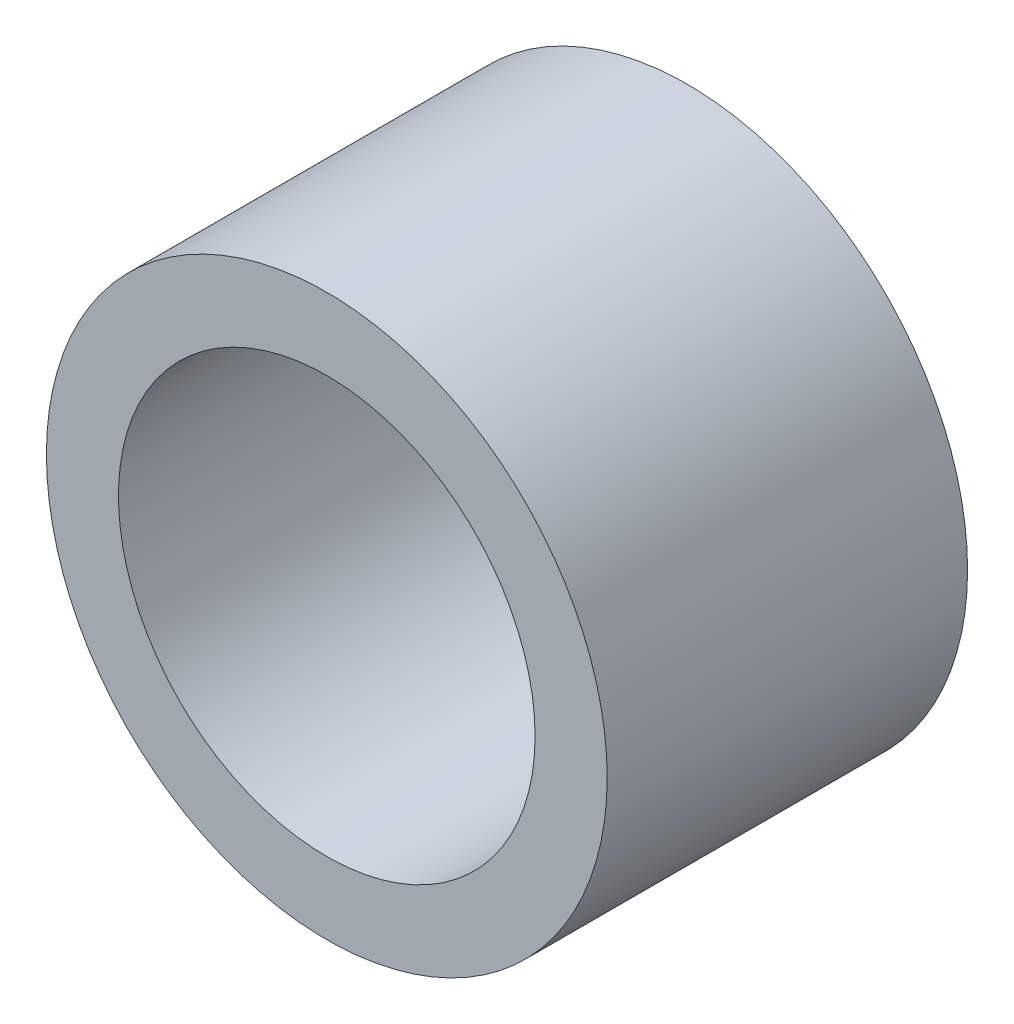
SolidWorks part; units mm, degrees
ref_plane "Piano frontale" through (0, 0, 0) normal (0, 0, 1) x (1, 0, 0)
ref_plane "Piano superiore" through (0, 0, 0) normal (0, 1, 0) x (1, 0, 0)
ref_plane "Piano destro" through (0, 0, 0) normal (1, 0, 0) x (0, 0, -1)
sketch "Schizzo1" plane through (0, 0, 0) normal (0, 0, 1) x (1, 0, 0)
  circle A0 centre (0, 0) radius 3.89
  circle A1 centre (0, 0) radius 2.89
  dimension "D1" = 5.78
  dimension "D2" = 1
extrude "Estrusione-Estrusione1" add sketch "Schizzo1" along normal blind 5
